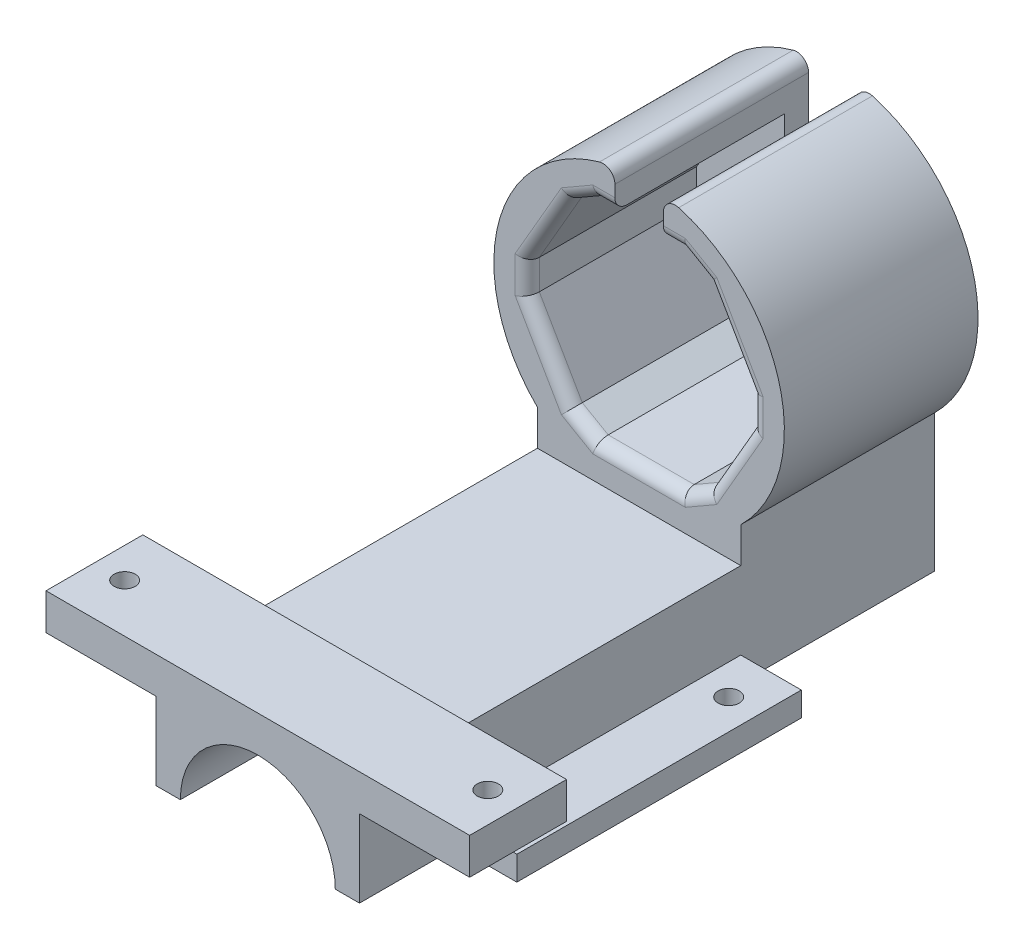
SolidWorks part; units mm, degrees
ref_plane "Front Plane" through (0, 0, 0) normal (1, 0, 0) x (0, 1, 0)
ref_plane "Top Plane" through (0, 0, 0) normal (0, 0, 1) x (0, 1, 0)
ref_plane "Right Plane" through (0, 0, 0) normal (0, 1, 0) x (-1, 0, 0)
sketch "Sketch1" plane through (0, 0, 0) normal (0, 0, 1) x (0, 1, 0)
  line L0 (16.8, -16.8) -> (16.8, 16.8)
  line L1 (16.8, 16.8) -> (4, 16.8)
  line L2 (4, 16.8) -> (4, 26.8)
  line L3 (4, 26.8) -> (0, 26.8)
  line L4 (0, 26.8) -> (0, 12.8)
  line L5 (0, -12.8) -> (0, -26.8)
  line L6 (0, -26.8) -> (4, -26.8)
  line L7 (4, -26.8) -> (4, -16.8)
  line L8 (4, -16.8) -> (16.8, -16.8)
  line L9 (0, 0) -> (16.8, 0) construction
  line L10 (12.8, 0) -> (12.8, 16.8) construction
  arc A0 (0, 12.8) -> (0, -12.8) centre (0, 0) cw
  dimension "D1" = 12.8
  dimension "D2" = 4
  dimension "D4" = 4
  dimension "D3" = 10
  dimension "D5" = 4
extrude "Boss-Extrude1" add sketch "Sketch1" along normal blind 95
sketch "Sketch2" plane through (0, 0, 0) normal (0, 0, -1) x (1, 0, 0)
  line L5 (0, 0) -> (0, -39.8) construction
  line L6 (-16.8, -16.8) -> (-16.8, -22.6606)
  line L7 (16.8, -16.8) -> (-16.8, -16.8) construction
  line L8 (-16.8, -16.8) -> (16.8, -16.8)
  line L9 (16.8, -16.8) -> (16.8, -22.6606)
  arc A0 (-16.8, -22.6606) -> (16.8, -22.6606) centre (0, -39.8) ccw
  dimension "D3" = 24
  dimension "D1" = 23
extrude "Boss-Extrude2" add sketch "Sketch2" against normal blind 32
sketch "Sketch3" plane through (0, 0, 0) normal (0, -1, 0) x (1, 0, 0)
  line L1 (-26.8, 95) -> (-16.8, 95)
  line L2 (-26.8, 95) -> (-26.8, 79)
  line L3 (-26.8, 79) -> (-16.8, 79)
  line L4 (-16.8, 95) -> (-16.8, 79)
  line L5 (0, 95) -> (0, 0) construction
  line L6 (12.8, 95) -> (-12.8, 95) construction
  line L8 (-26.8, 0) -> (-16.8, 0)
  line L9 (-26.8, 0) -> (-26.8, 32)
  line L10 (-26.8, 32) -> (-16.8, 32)
  line L11 (-16.8, 0) -> (-16.8, 32)
  line L13 (26.8, 32) -> (16.8, 32)
  line L14 (16.8, 0) -> (16.8, 32)
  line L15 (26.8, 0) -> (16.8, 0)
  line L16 (26.8, 0) -> (26.8, 32)
  line L17 (26.8, 79) -> (16.8, 79)
  line L18 (16.8, 95) -> (16.8, 79)
  line L19 (26.8, 95) -> (16.8, 95)
  line L20 (26.8, 95) -> (26.8, 79)
  line L21 (-12.8, 95) -> (-12.8, 0) construction
  line L22 (24, 32) -> (-24, 32) construction
  dimension "D1" = 16
  dimension "D2" = 4
extrude "Cut-Extrude1" cut sketch "Sketch3" against normal up to surface (4 mm away) up to face at (-21.8, 4, 47.5)
sketch "Sketch4" plane through (0, 0, 32) normal (0, 0, 1) x (1, 0, 0)
  line L0 (-19.91, 39.8) -> (0, 39.8) construction
  line L1 (-11.38, 54.5744) -> (-18.485, 42.2682)
  line L2 (-18.485, 37.3318) -> (-11.38, 25.0256)
  line L3 (-7.105, 22.5574) -> (7.105, 22.5574)
  line L4 (11.38, 25.0256) -> (18.485, 37.3318)
  line L5 (18.485, 42.2682) -> (11.38, 54.5744)
  line L6 (7.105, 57.0426) -> (-7.105, 57.0426)
  line L7 (-7.105, 57.0426) -> (-11.38, 54.5744)
  line L8 (-18.485, 42.2682) -> (-18.485, 37.3318)
  line L9 (18.485, 37.3318) -> (18.485, 42.2682)
  line L10 (11.38, 54.5744) -> (7.105, 57.0426)
  line L11 (7.105, 22.5574) -> (11.38, 25.0256)
  line L12 (-11.38, 25.0256) -> (-7.105, 22.5574)
  circle A0 centre (0, 39.8) radius 17.2426 construction
  point P2 (-9.955, 57.0426)
  point P4 (-9.955, 22.5574)
  point P5 (9.955, 22.5574)
  point P6 (19.91, 39.8)
  point P7 (9.955, 57.0426)
  dimension "D1" = 19.91
extrude "Cut-Extrude2" cut sketch "Sketch4" against normal blind 28
sketch "Sketch5" plane through (0, 16.8, 0) normal (0, 1, 0) x (-1, 0, 0)
  line L0 (-26.8, 79) -> (-16.8, 79) construction
  line L1 (-35, 95) -> (35, 95)
  line L2 (-35, 95) -> (-35, 79)
  line L3 (-35, 79) -> (35, 79)
  line L4 (35, 95) -> (35, 79)
  line L5 (-16.8, 95) -> (16.8, 95) construction
  line L7 (0, 95) -> (0, 32) construction
  line L8 (24, 32) -> (-24, 32) construction
  dimension "D1" = 70
extrude "Boss-Extrude3" add sketch "Sketch5" against normal blind 4 and the other way blind 2
sketch "Sketch6" plane through (0, 18.8, 0) normal (0, 1, 0) x (-1, 0, 0)
  line L0 (0, 95) -> (0, 79) construction
  line L1 (35, 95) -> (-35, 95) construction
  line L2 (-35, 79) -> (35, 79) construction
  line L3 (-35, 87) -> (0, 87) construction
  line L4 (-35, 95) -> (-35, 79) construction
  circle A0 centre (-30, 87) radius 1.75
  circle A1 centre (30, 87) radius 1.75
  dimension "D2" = 3.5
  dimension "D1" = 30
extrude "Cut-Extrude3" cut sketch "Sketch6" against normal through all
sketch "Sketch7" plane through (0, 4, 0) normal (0, 1, 0) x (-1, 0, 0)
  line L0 (-21.8, 79) -> (-21.8, 32) construction
  line L1 (-26.8, 79) -> (-16.8, 79) construction
  line L2 (-16.8, 32) -> (-26.8, 32) construction
  line L3 (0, 79) -> (0, 32) construction
  line L4 (-16.8, 79) -> (16.8, 79) construction
  line L5 (-16.8, 32) -> (16.8, 32) construction
  line L6 (-35, 79) -> (35, 79) construction
  line L7 (24, 32) -> (-24, 32) construction
  circle A0 centre (-21.8, 72) radius 1.75
  circle A1 centre (-21.8, 39) radius 1.75
  circle A2 centre (21.8, 39) radius 1.75
  circle A3 centre (21.8, 72) radius 1.75
  dimension "D3" = 3.5
  dimension "D1" = 7
  dimension "D2" = 7
  dimension "D4" = 21.8
extrude "Cut-Extrude4" cut sketch "Sketch7" against normal through all
sketch "Sketch8" plane through (0, 0, 4) normal (0, 0, 1) x (1, 0, 0)
  line L0 (0, 57.0426) -> (0, 22.5574) construction
  line L1 (7.105, 57.0426) -> (-7.105, 57.0426) construction
  line L2 (-7.105, 22.5574) -> (7.105, 22.5574) construction
  line L4 (-4, 35.8) -> (4, 35.8)
  line L5 (-4, 35.8) -> (-4, 63.4643)
  line L7 (4, 35.8) -> (4, 63.4643)
  arc A0 (-4, 63.4643) -> (4, 63.4643) centre (0, 39.8) cw
  arc A1 (16.8, 22.6606) -> (-16.8, 22.6606) centre (0, 39.8) ccw construction
  point P6 (0, 39.8)
  point P15 (0, 0)
  point P16 (0, 0)
  dimension "D1" = 4
  dimension "D2" = 8
extrude "Cut-Extrude5" cut sketch "Sketch8" against normal through all and the other way through all
fillet "Fillet1" radius 2 15 edges at (4, 63.4643, 16) (-4, 63.4643, 16) (-9.2425, 23.7915, 32) (-14.9325, 31.1787, 32) (-18.485, 39.8, 32) (-14.9325, 48.4213, 32) (-9.2425, 55.8085, 32) (-5.5525, 57.0426, 32) (5.5525, 57.0426, 32) (18.485, 39.8, 32) (14.9325, 48.4213, 32) (9.2425, 55.8085, 32) (14.9325, 31.1787, 32) (9.2425, 23.7915, 32) (0, 22.5574, 32)
